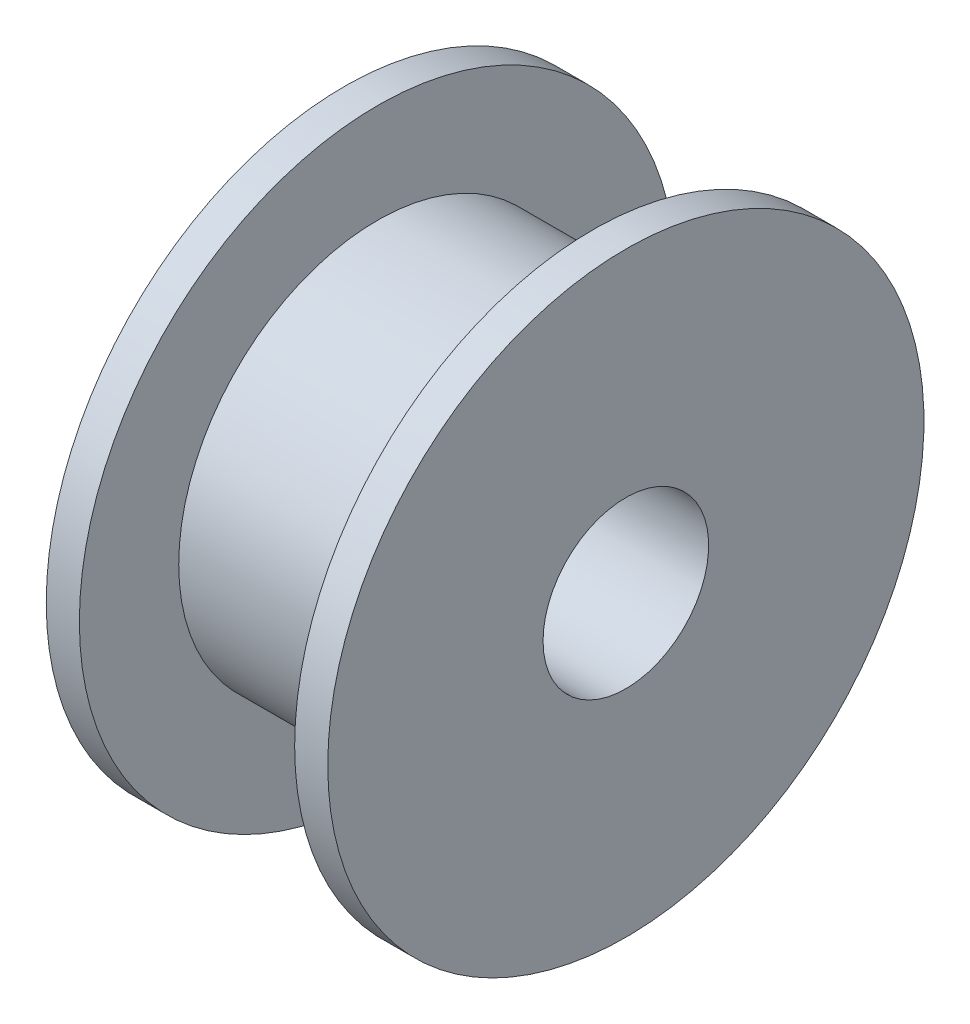
SolidWorks part; units mm, degrees
material "1060 Alloy"
ref_plane "Front Plane" through (0, 0, 0) normal (0, 0, 1) x (1, 0, 0)
ref_plane "Top Plane" through (0, 0, 0) normal (0, 1, 0) x (1, 0, 0)
ref_plane "Right Plane" through (0, 0, 0) normal (1, 0, 0) x (0, 0, -1)
sketch "MainSketch" plane through (0, 0, 0) normal (0, 0, 1) x (1, 0, 0)
  line L0 (-4.25, 0) -> (4.25, 0) construction
  line L1 (-4.25, 2.5) -> (4.25, 2.5)
  line L2 (4.25, 2.5) -> (4.25, 9)
  line L3 (4.25, 9) -> (3.25, 9)
  line L4 (3.25, 9) -> (3.25, 6)
  line L5 (3.25, 6) -> (-3.25, 6)
  line L6 (-3.25, 6) -> (-3.25, 9)
  line L7 (-3.25, 9) -> (-4.25, 9)
  line L8 (-4.25, 9) -> (-4.25, 2.5)
  point P4 (0, 0)
  point P7 (0, 0)
  point P14 (0, 0)
  point P15 (4.25, 0)
  point P16 (0, 0)
  point P17 (0, 0)
  dimension "D1" = 8.5
  dimension "D2" = 6.5
  dimension "D3" = 9
  dimension "D4" = 6
  dimension "D5" = 2.5
revolve "MainRevolve" add sketch "MainSketch" angle 360 about L0
